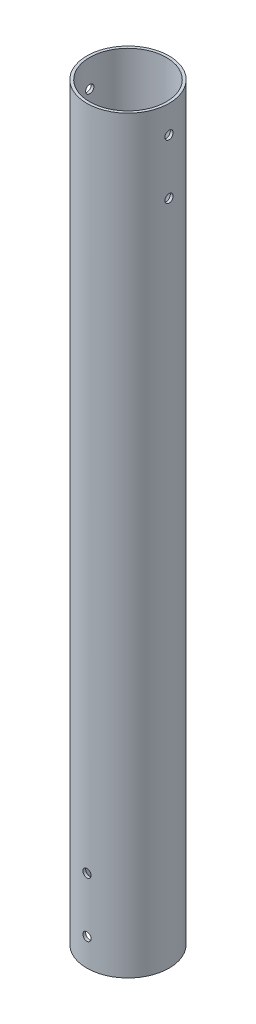
SolidWorks part; units mm, degrees
ref_plane "前基準面" through (0, 0, 0) normal (0, 0, 1) x (1, 0, 0)
ref_plane "上基準面" through (0, 0, 0) normal (0, 1, 0) x (1, 0, 0)
ref_plane "右基準面" through (0, 0, 0) normal (1, 0, 0) x (0, 0, -1)
sketch "草圖1" plane through (0, 0, 0) normal (0, 1, 0) x (1, 0, 0)
  circle A0 centre (0, 0) radius 15
  dimension "D1" = 30
extrude "填料-伸長1" add sketch "草圖1" along normal blind 273
sketch "草圖2" plane through (0, 0, 0) normal (0, 0, 1) x (1, 0, 0)
  circle A0 centre (0, 10) radius 1.5
  circle A1 centre (0, 30) radius 1.5
  dimension "D1" = 3
  dimension "D3" = 10
  dimension "D4" = 20
extrude "除料-伸長1" cut sketch "草圖2" against normal through all both and the other way through all
sketch "草圖3" plane through (0, 0, 0) normal (1, 0, 0) x (0, 0, -1)
  line L0 (15, 273) -> (-15, 273) construction
  circle A0 centre (0, 263) radius 1.5
  circle A1 centre (0, 243) radius 1.5
  dimension "D1" = 3
  dimension "D2" = 10
  dimension "D3" = 20
extrude "除料-伸長2" cut sketch "草圖3" against normal through all both and the other way through all
sketch "草圖4" plane through (0, 273, 0) normal (0, 1, 0) x (1, 0, 0)
  circle A2 centre (0, 0) radius 14
  circle A3 centre (0, 0) radius 14
  dimension "D1" = 1
extrude "除料-伸長3" cut sketch "草圖4" against normal up to next
